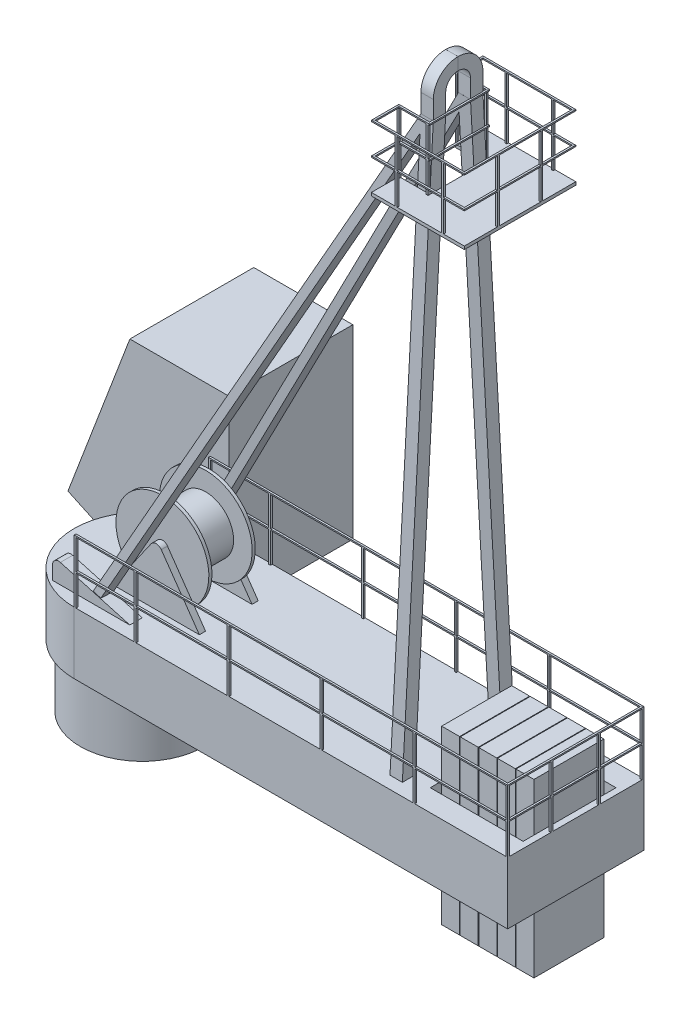
SolidWorks part; units mm, degrees
ref_plane "Front Plane" through (0, 0, 0) normal (0, 0, 1) x (1, 0, 0)
ref_plane "Top Plane" through (0, 0, 0) normal (0, 1, 0) x (1, 0, 0)
ref_plane "Right Plane" through (0, 0, 0) normal (1, 0, 0) x (0, 0, -1)
sketch "Sketch1" plane through (0, 0, 0) normal (0, 1, 0) x (1, 0, 0)
  circle A0 centre (0, 0) radius 1000
  dimension "D1" = 2000
extrude "Boss-Extrude1" add sketch "Sketch1" along normal blind 1000
sketch "Sketch2" plane through (0, 1000, 0) normal (0, 1, 0) x (1, 0, 0)
  line L1 (7000, -1100) -> (0, -1100)
  line L2 (7000, -1100) -> (7000, 1100)
  line L3 (7000, 1100) -> (0, 1100)
  line L5 (5400, -750) -> (6900, -750)
  line L6 (5400, -750) -> (5400, 750)
  line L7 (5400, 750) -> (6900, 750)
  line L8 (6900, -750) -> (6900, 750)
  line L9 (5400, -750) -> (6900, 750) construction
  line L10 (5400, 750) -> (6900, -750) construction
  circle A2 centre (0, 0) radius 1100
  arc A3 (0, 1100) -> (0, -1100) centre (0, 0) ccw
  point P0 (1484.5007, 0)
  point P6 (6150, 0)
  dimension "D2" = 7000
  dimension "D3" = 7000
  dimension "D4" = 1500
  dimension "D5" = 1500
  dimension "D6" = 100
extrude "Boss-Extrude2" add sketch "Sketch2" along normal blind 1000
sketch "Sketch3" plane through (5400, 0, 0) normal (1, 0, 0) x (0, 0, -1)
  line L1 (-565.5574, -8.1645) -> (565.5574, -8.1645)
  line L2 (-565.5574, -8.1645) -> (-565.5574, 2768.8659)
  line L3 (-565.5574, 2768.8659) -> (565.5574, 2768.8659)
  line L4 (565.5574, -8.1645) -> (565.5574, 2768.8659)
  line L5 (-565.5574, -8.1645) -> (565.5574, 2768.8659) construction
  line L6 (-565.5574, 2768.8659) -> (565.5574, -8.1645) construction
  point P0 (0, 1380.3507)
extrude "Boss-Extrude3" add sketch "Sketch3" along normal blind 290 separate body
pattern_linear "LPattern1" count 5 spacing 300 along (1, 0, 0) of "Boss-Extrude3"
ref_plane "Plane1" through (4900, 0, 0) normal (1, 0, 0) x (0, 0, -1)
sketch "Sketch4" plane through (4900, 0, 0) normal (1, 0, 0) x (0, 0, -1)
  line L0 (-900, 2000) -> (-400.308, 11000)
  line L1 (-400.308, 11000) -> (-200, 11000)
  line L2 (-200, 11000) -> (-699.692, 2000)
  line L3 (-1100, 2000) -> (1100, 2000) construction
  line L4 (-699.692, 2000) -> (-900, 2000)
  line L5 (-400.308, 11000) -> (-400.308, 11300)
  line L6 (-200.308, 11000) -> (-200.308, 11300)
  line L7 (-0.157, 11700.151) -> (-0.157, 11500.151)
  line L8 (-1100, 2000) -> (-1100, 1000) construction
  arc A0 (-400.308, 11300) -> (-0.157, 11700.151) centre (-0.157, 11300) cw
  arc A1 (-200.308, 11300) -> (-0.157, 11500.151) centre (-0.157, 11300) cw
  dimension "D1" = 9000
  dimension "D2" = 200
  dimension "D3" = 200
  dimension "D5" = 300
  dimension "D6" = 200
  dimension "D4" = 200
extrude "Boss-Extrude4" add sketch "Sketch4" along normal blind 200 contours L6 A1 L7 A0 L5 L1 | L4 L2 L1 L0
ref_plane "Plane2" through (0, 55.9619, 1007.9356) normal (0, 0.0554, 0.9985) x (1, 0, 0)
sketch "Sketch5" plane through (0, 55.9619, 1007.9356) normal (0, 0.0554, 0.9985) x (1, 0, 0)
  line L0 (0, 1935.9449) -> (4900, 10960.8932)
  line L1 (4900, 10960.8932) -> (4900, 10693.5077)
  line L2 (4900, 10693.5077) -> (145.1742, 1935.9449)
  line L3 (145.1742, 1935.9449) -> (0, 1935.9449)
  line L15 (0, 1935.9449) -> (0, 937.4827) construction
  line L18 (0, 1935.9449) -> (7000, 1935.9449) construction
  line L19 (4900, 1947.0321) -> (4900, 10960.8932) construction
extrude "Boss-Extrude6" add sketch "Sketch5" against normal blind 200
ref_plane "Plane3" through (0, 2800, 0) normal (0, 1, 0) x (1, 0, 0)
sketch "Sketch6" plane through (0, 2800, 0) normal (0, 1, 0) x (1, 0, 0)
  line L0 (700, 375) -> (700, -375)
  line L1 (700, -375) -> (1450, -375)
  line L2 (1450, -375) -> (1450, -325)
  line L3 (1450, -325) -> (1150, -325)
  line L4 (1150, -325) -> (1150, 325)
  line L5 (1150, 325) -> (1450, 325)
  line L6 (1450, 325) -> (1450, 375)
  line L7 (1450, 375) -> (700, 375)
  point P2 (700, 0)
  dimension "D1" = 700
  dimension "D2" = 750
  dimension "D3" = 750
  dimension "D4" = 300
  dimension "D5" = 750
  dimension "D6" = 50
  dimension "D7" = 50
revolve "Revolve1" add sketch "Sketch6" angle 360 about L0
sketch "Sketch7" plane through (0, 0, 375) normal (0, 0, 1) x (1, 0, 0)
  line L0 (0, 2000) -> (617.8994, 2882.7134)
  line L1 (781.8621, 2882.5469) -> (1396.9772, 2000)
  line L2 (0, 2000) -> (7000, 2000) construction
  line L3 (0, 2000) -> (1396.9772, 2000)
  arc A1 (781.8621, 2882.5469) -> (617.8994, 2882.7134) centre (699.8226, 2825.3672) ccw
  point P12 (700, 3000)
  dimension "D2" = 1218.9246
  dimension "D3" = 100
  dimension "D1" = 1000
extrude "Boss-Extrude7" add sketch "Sketch7" along normal blind 100
ref_plane "Plane4" through (0, 0, 900) normal (0, 0, 1) x (1, 0, 0)
sketch "Sketch8" plane through (0, 0, 900) normal (0, 0, 1) x (1, 0, 0)
  line L0 (-550, 2000) -> (-550, 2218.1109)
  line L1 (0, 2000) -> (-1100, 2000) construction
  line L2 (-423.0067, 2314.3988) -> (698.4886, 2000)
  line L3 (0, 2000) -> (1396.9772, 2000) construction
  line L4 (-550, 2000) -> (698.4886, 2000)
  arc A0 (-423.0067, 2314.3988) -> (-550, 2218.1109) centre (-450, 2218.1109) ccw
  point P10 (-550, 2350)
  dimension "D2" = 100
  dimension "D1" = 350
extrude "Boss-Extrude8" add sketch "Sketch8" against normal blind 200
mirror "Mirror1" about plane through (0, 0, 0) normal (0, 0, 1) of "Boss-Extrude8", "Boss-Extrude6", "Boss-Extrude4", "Boss-Extrude7"
ref_plane "Plane5" through (0, 10000, 0) normal (0, 1, 0) x (1, 0, 0)
sketch "Sketch9" plane through (0, 10000, 0) normal (0, 1, 0) x (1, 0, 0)
  line L0 (5100, -455.8294) -> (4600, -455.8294)
  line L2 (4600, -455.8294) -> (4600, -900)
  line L3 (-1210, -900) -> (1210, -900) construction
  line L4 (4600, -900) -> (6100, -900)
  line L5 (6100, -900) -> (6100, 900)
  line L6 (6100, 900) -> (4600, 900)
  line L7 (4600, 900) -> (4600, 455.8294)
  line L8 (4600, 455.8294) -> (5100, 455.8294)
  line L10 (5100, 455.8294) -> (5100, -455.8294)
  dimension "D1" = 1000
  dimension "D2" = 500
  dimension "D3" = 500
extrude "Boss-Extrude9" add sketch "Sketch9" against normal blind 50
sketch "Sketch10" plane through (0, 10000, 0) normal (0, 1, 0) x (1, 0, 0)
  line L0 (6100, -900) -> (6100, 900) construction
  line L1 (6070, -365) -> (6100, -365)
  line L2 (6070, -365) -> (6070, -335)
  line L3 (6070, -335) -> (6100, -335)
  line L4 (6100, -365) -> (6100, -335)
  line L5 (6070, -365) -> (6100, -335) construction
  line L6 (6070, -335) -> (6100, -365) construction
  line L7 (4600, -900) -> (6100, -900) construction
  line L8 (5765, -870) -> (5735, -870)
  line L9 (5765, -870) -> (5765, -900)
  line L10 (5765, -900) -> (5735, -900)
  line L11 (5735, -870) -> (5735, -900)
  line L12 (5765, -870) -> (5735, -900) construction
  line L13 (5765, -900) -> (5735, -870) construction
  line L19 (-4455, 0) -> (4455, 0) construction
  line L20 (5015, -870) -> (4985, -870)
  line L21 (5015, -870) -> (5015, -900)
  line L22 (5015, -900) -> (4985, -900)
  line L23 (4985, -870) -> (4985, -900)
  line L24 (5015, -870) -> (4985, -900) construction
  line L25 (5015, -900) -> (4985, -870) construction
  line L26 (5015, 900) -> (4985, 870) construction
  line L27 (5015, 870) -> (4985, 900) construction
  line L28 (5765, 900) -> (5735, 870) construction
  line L29 (5765, 870) -> (5735, 900) construction
  line L30 (6070, 335) -> (6100, 365) construction
  line L31 (6070, 365) -> (6100, 335) construction
  line L32 (4985, 870) -> (4985, 900)
  line L33 (5015, 900) -> (4985, 900)
  line L34 (5015, 870) -> (5015, 900)
  line L35 (5015, 870) -> (4985, 870)
  line L36 (5735, 870) -> (5735, 900)
  line L37 (5765, 900) -> (5735, 900)
  line L38 (5765, 870) -> (5765, 900)
  line L39 (5765, 870) -> (5735, 870)
  line L40 (6100, 365) -> (6100, 335)
  line L41 (6070, 335) -> (6100, 335)
  line L42 (6070, 365) -> (6070, 335)
  line L43 (6070, 365) -> (6100, 365)
  line L44 (5070, 455.8294) -> (5100, 485.8294) construction
  line L45 (4630, -485.8294) -> (4600, -485.8294)
  line L46 (4630, -485.8294) -> (4630, -455.8294)
  line L47 (4630, -455.8294) -> (4600, -455.8294)
  line L48 (4600, -485.8294) -> (4600, -455.8294)
  line L49 (4630, -485.8294) -> (4600, -455.8294) construction
  line L50 (4630, -455.8294) -> (4600, -485.8294) construction
  line L51 (5070, -485.8294) -> (5100, -485.8294)
  line L52 (5070, -485.8294) -> (5070, -455.8294)
  line L53 (5070, -455.8294) -> (5100, -455.8294)
  line L54 (5100, -485.8294) -> (5100, -455.8294)
  line L55 (5070, -485.8294) -> (5100, -455.8294) construction
  line L56 (5070, -455.8294) -> (5100, -485.8294) construction
  line L57 (5070, 485.8294) -> (5100, 455.8294) construction
  line L58 (4630, 455.8294) -> (4600, 485.8294) construction
  line L59 (4630, 485.8294) -> (4600, 455.8294) construction
  line L60 (5100, 485.8294) -> (5100, 455.8294)
  line L61 (5070, 455.8294) -> (5100, 455.8294)
  line L62 (5070, 485.8294) -> (5070, 455.8294)
  line L63 (5070, 485.8294) -> (5100, 485.8294)
  line L64 (4600, 485.8294) -> (4600, 455.8294)
  line L65 (4630, 455.8294) -> (4600, 455.8294)
  line L66 (4630, 485.8294) -> (4630, 455.8294)
  line L67 (4630, 485.8294) -> (4600, 485.8294)
  point P0 (6085, -350)
  point P7 (5750, -885)
  point P14 (5000, -885)
  point P34 (5000, 885)
  point P35 (5750, 885)
  point P36 (6085, 350)
  point P37 (4615, -470.8294)
  point P43 (5085, -470.8294)
  point P57 (5085, 470.8294)
  point P58 (4615, 470.8294)
  dimension "D1" = 30
  dimension "D2" = 30
  dimension "D3" = 30
  dimension "D4" = 30
  dimension "D5" = 30
  dimension "D6" = 30
  dimension "D7" = 350
  dimension "D8" = 350
  dimension "D9" = 750
  dimension "D10" = 30
  dimension "D11" = 30
  dimension "D12" = 30
  dimension "D13" = 30
extrude "Boss-Extrude10" add sketch "Sketch10" along normal blind 1000
sketch "Sketch11" plane through (0, 11000, 0) normal (0, 1, 0) x (1, 0, 0)
  line L0 (5110, -470.8294) -> (4615, -470.8294)
  line L3 (4615, -470.8294) -> (4615, -885)
  line L5 (4615, -885) -> (6085, -885)
  line L6 (6085, -885) -> (6085, 885)
  line L7 (6085, 885) -> (4615, 885)
  line L8 (4615, 885) -> (4615, 470.8294)
  line L9 (4615, 470.8294) -> (5110, 470.8294)
  line L10 (5110, 470.8294) -> (5110, -470.8294)
  line L11 (4985, 900) -> (4985, 870) construction
  line L12 (4630, 485.8294) -> (4600, 485.8294) construction
  line L14 (5070, 485.8294) -> (5070, 455.8294) construction
  line L16 (4630, -485.8294) -> (4630, -455.8294) construction
  line L17 (4600, -485.8294) -> (4630, -485.8294) construction
  line L19 (5015, -900) -> (5015, -870) construction
  line L20 (6070, -365) -> (6100, -365) construction
  line L21 (5100, -485.8294) -> (5100, -455.8294) construction
  point P5 (4630, -470.8294)
  point P22 (4985, 885)
  point P26 (4615, 485.8294)
  point P29 (5070, 470.8294)
  point P32 (4615, -485.8294)
  point P33 (5015, -885)
  point P36 (6085, -365)
  dimension "D1" = 10
sketch "Sketch19" plane through (0, 0, 485.8294) normal (0, 0, 1) x (1, 0, 0)
  line L0 (4600, 11000) -> (4630, 11000) construction
  line L1 (4600, 11010) -> (4630, 11010)
  line L2 (4600, 11010) -> (4600, 10990)
  line L3 (4600, 10990) -> (4630, 10990)
  line L4 (4630, 11010) -> (4630, 10990)
  line L5 (4600, 11010) -> (4630, 10990) construction
  line L6 (4600, 10990) -> (4630, 11010) construction
  line L7 (4630, 11000) -> (4630, 10000) construction
  point P0 (4615, 11000)
  dimension "D1" = 20
sweep "Sweep3" add profiles "Sketch19" path "Sketch11"
sketch "Sketch20" plane through (0, 2000, 0) normal (0, 1, 0) x (1, 0, 0)
  line L0 (5470, -1070) -> (5470, -1100)
  line L1 (6970, -1070) -> (7000, -1070)
  line L2 (6970, -1070) -> (6970, -1100)
  line L3 (6970, -1100) -> (7000, -1100)
  line L4 (7000, -1070) -> (7000, -1100)
  line L5 (6970, -1070) -> (7000, -1100) construction
  line L6 (6970, -1100) -> (7000, -1070) construction
  line L7 (5470, -1070) -> (5500, -1070)
  line L8 (5500, -1070) -> (5500, -1100)
  line L9 (5470, -1100) -> (5500, -1100)
  line L10 (3970, -1070) -> (3970, -1100)
  line L11 (3970, -1070) -> (4000, -1070)
  line L12 (4000, -1070) -> (4000, -1100)
  line L13 (3970, -1100) -> (4000, -1100)
  line L14 (2470, -1070) -> (2470, -1100)
  line L15 (2470, -1070) -> (2500, -1070)
  line L16 (2500, -1070) -> (2500, -1100)
  line L17 (2470, -1100) -> (2500, -1100)
  line L18 (970, -1070) -> (970, -1100)
  line L19 (970, -1070) -> (1000, -1070)
  line L20 (1000, -1070) -> (1000, -1100)
  line L21 (970, -1100) -> (1000, -1100)
  line L22 (6970, -370) -> (6970, -400)
  line L23 (30, -1070) -> (0, -1070)
  line L24 (30, -1070) -> (30, -1100)
  line L25 (30, -1100) -> (0, -1100)
  line L26 (0, -1070) -> (0, -1100)
  line L27 (30, -1070) -> (0, -1100) construction
  line L28 (30, -1100) -> (0, -1070) construction
  line L29 (6970, -370) -> (7000, -370)
  line L30 (7000, -370) -> (7000, -400)
  line L31 (6970, -400) -> (7000, -400)
  line L33 (-4455, 0) -> (4455, 0) construction
  line L34 (30, 1100) -> (0, 1070) construction
  line L35 (30, 1070) -> (0, 1100) construction
  line L36 (6970, 1100) -> (7000, 1070) construction
  line L37 (6970, 1070) -> (7000, 1100) construction
  line L38 (6970, 400) -> (7000, 400)
  line L39 (7000, 370) -> (7000, 400)
  line L40 (6970, 370) -> (7000, 370)
  line L41 (0, 1070) -> (0, 1100)
  line L42 (30, 1100) -> (0, 1100)
  line L43 (30, 1070) -> (30, 1100)
  line L44 (30, 1070) -> (0, 1070)
  line L45 (6970, 370) -> (6970, 400)
  line L46 (970, 1100) -> (1000, 1100)
  line L47 (1000, 1070) -> (1000, 1100)
  line L48 (970, 1070) -> (1000, 1070)
  line L49 (970, 1070) -> (970, 1100)
  line L50 (2470, 1100) -> (2500, 1100)
  line L51 (2500, 1070) -> (2500, 1100)
  line L52 (2470, 1070) -> (2500, 1070)
  line L53 (2470, 1070) -> (2470, 1100)
  line L54 (3970, 1100) -> (4000, 1100)
  line L55 (4000, 1070) -> (4000, 1100)
  line L56 (3970, 1070) -> (4000, 1070)
  line L57 (3970, 1070) -> (3970, 1100)
  line L58 (5470, 1100) -> (5500, 1100)
  line L59 (5500, 1070) -> (5500, 1100)
  line L60 (5470, 1070) -> (5500, 1070)
  line L61 (5470, 1070) -> (5470, 1100)
  line L62 (6970, 1100) -> (7000, 1100)
  line L63 (7000, 1070) -> (7000, 1100)
  line L64 (6970, 1070) -> (7000, 1070)
  line L65 (6970, 1070) -> (6970, 1100)
  point P0 (6985, -1085)
  point P6 (15, -1085)
  point P64 (15, 1085)
  point P65 (6985, 1085)
  dimension "D1" = 30
  dimension "D2" = 30
  dimension "D4" = 30
  dimension "D5" = 30
  dimension "D3" = 5
  dimension "D6" = 2
extrude "Boss-Extrude11" add sketch "Sketch20" along normal blind 1000
pattern_linear "LPattern2" count 2 spacing 500 along (0, -1, 0) of "Sweep3"
sketch "Sketch21" plane through (0, 3000, 0) normal (0, 1, 0) x (1, 0, 0)
  line L0 (0, -1085) -> (6985, -1085)
  line L1 (0, -1070) -> (0, -1100) construction
  line L2 (6985, -1085) -> (6985, 1085)
  line L3 (6985, 1085) -> (0, 1085)
  line L4 (0, 1100) -> (0, 1070) construction
sketch "Sketch22" plane through (0, 0, 0) normal (-1, 0, 0) x (0, 0, 1)
  line L0 (1100, 3000) -> (1100, 2000) construction
  line L1 (1070, 3010) -> (1100, 3010)
  line L2 (1070, 3010) -> (1070, 2990)
  line L3 (1070, 2990) -> (1100, 2990)
  line L4 (1100, 3010) -> (1100, 2990)
  line L5 (1070, 3010) -> (1100, 2990) construction
  line L6 (1070, 2990) -> (1100, 3010) construction
  point P0 (1085, 3000)
  dimension "D1" = 20
sweep "Sweep4" add profiles "Sketch22" path "Sketch21"
pattern_linear "LPattern3" count 2 spacing 500 along (0, -1, 0) of "Sweep4"
ref_plane "Plane6" through (0, 0, 0) normal (1, 0, 0) x (0, 0, -1)
sketch "Sketch23" plane through (0, 0, 0) normal (1, 0, 0) x (0, 0, -1)
  line L0 (-1100, 1000) -> (1100, 1000) construction
  line L1 (3100, 4000) -> (1100, 4000)
  line L2 (3100, 4000) -> (3100, 1000)
  line L3 (3100, 1000) -> (1100, 1000)
  line L4 (1100, 4000) -> (1100, 1000)
  line L5 (3100, 4000) -> (1100, 1000) construction
  line L6 (3100, 1000) -> (1100, 4000) construction
  line L7 (1100, 2000) -> (1100, 1000) construction
  point P0 (2100, 2500)
  dimension "D1" = 3000
  dimension "D2" = 2000
extrude "Boss-Extrude12" add sketch "Sketch23" along normal mid plane 600
sketch "Sketch24" plane through (0, 0, -3100) normal (0, 0, -1) x (-1, 0, 0)
  line L0 (300, 4000) -> (1300, 4000)
  line L1 (1300, 4000) -> (2300, 1373.0461)
  line L2 (2300, 1373.0461) -> (1500, 1000)
  line L3 (1500, 1000) -> (300, 1000)
  line L4 (300, 1000) -> (300, 4000)
  dimension "D1" = 1000
  dimension "D2" = 1200
  dimension "D3" = 2000
  dimension "D4" = 25
extrude "Boss-Extrude13" add sketch "Sketch24" along direction (0, 0, -1) on the side against the normal up to vertex (2000 mm away)
equation "\"D3@Sketch2\"=\"D2@Sketch2\""
equation "\"D3@Sketch6\"=\"D2@Sketch6\""
equation "\"D7@Sketch6\"=\"D6@Sketch6\""
equation "\"D3@Sketch9\"=\"D2@Sketch9\""
equation "\"D2@Sketch10\"=\"D1@Sketch10\""
equation "\"D3@Sketch10\"=\"D1@Sketch10\""
equation "\"D4@Sketch10\"=\"D1@Sketch10\""
equation "\"D5@Sketch10\"=\"D1@Sketch10\""
equation "\"D6@Sketch10\"=\"D1@Sketch10\""
equation "\"D10@Sketch10\"=\"D1@Sketch10\""
equation "\"D11@Sketch10\"=\"D1@Sketch10\""
equation "\"D12@Sketch10\"=\"D1@Sketch10\""
equation "\"D13@Sketch10\"=\"D1@Sketch10\""
